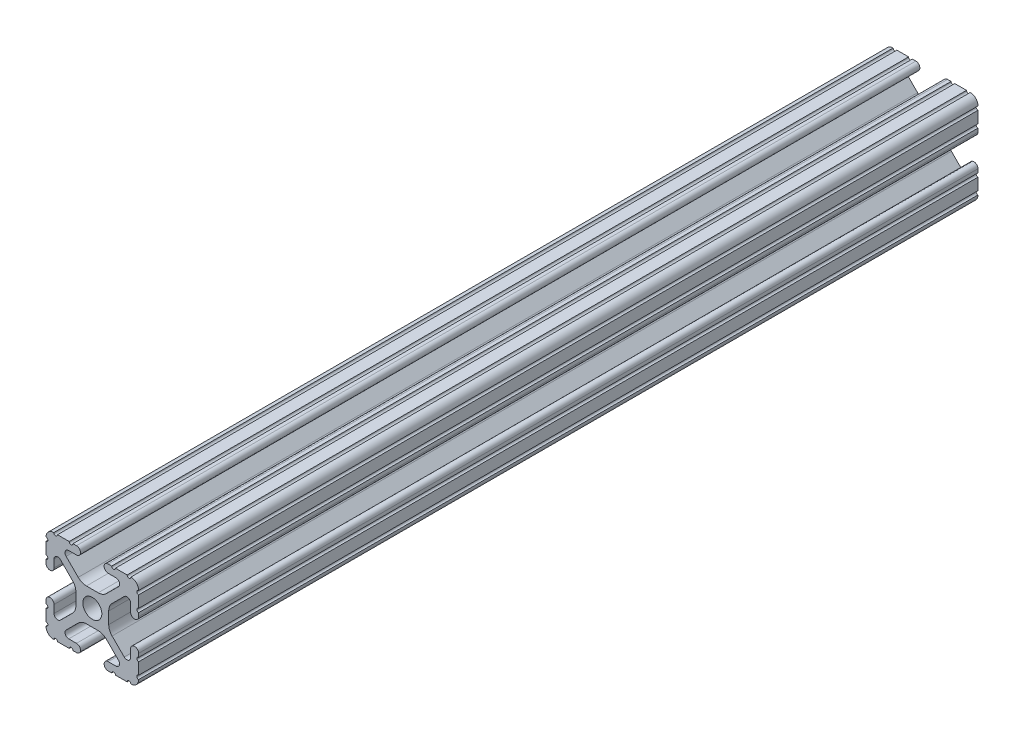
SolidWorks part; units mm, degrees
ref_plane "Front Plane" through (0, 0, 0) normal (0, 0, 1) x (1, 0, 0)
ref_plane "Top Plane" through (0, 0, 0) normal (0, 1, 0) x (1, 0, 0)
ref_plane "Right Plane" through (0, 0, 0) normal (1, 0, 0) x (0, 0, -1)
ref_plane "Plane1" through (0, 0, -25.4) normal (0, 0, -1) x (-1, 0, 0)
sketch "Sketch1" plane through (0, 0, -25.4) normal (0, 0, -1) x (-1, 0, 0)
  line L0 (12.7, -9.5504) -> (12.7, -6.3331)
  line L1 (12.7, -5.3171) -> (12.7, -4.3434)
  line L2 (10.4902, -4.3434) -> (10.4902, -6.4748)
  line L3 (8.7558, -7.1932) -> (5.4257, -3.8632)
  line L4 (4.4958, -1.6181) -> (4.4958, 1.6181)
  line L5 (5.4257, 3.8632) -> (8.7558, 7.1932)
  line L6 (10.4902, 6.4748) -> (10.4902, 4.3434)
  line L7 (12.7, 4.3434) -> (12.7, 5.3171)
  line L8 (12.7, 6.3331) -> (12.7, 9.5504)
  line L9 (9.5504, 12.7) -> (6.3331, 12.7)
  line L10 (5.3171, 12.7) -> (4.3434, 12.7)
  line L11 (4.3434, 10.4902) -> (6.4748, 10.4902)
  line L12 (7.1932, 8.7558) -> (3.8632, 5.4257)
  line L13 (1.6181, 4.4958) -> (-1.6181, 4.4958)
  line L14 (-3.8632, 5.4257) -> (-7.1932, 8.7558)
  line L15 (-6.4748, 10.4902) -> (-4.3434, 10.4902)
  line L16 (-4.3434, 12.7) -> (-5.3171, 12.7)
  line L17 (-6.3331, 12.7) -> (-9.5504, 12.7)
  line L18 (-12.7, 9.5504) -> (-12.7, 6.3331)
  line L19 (-12.7, 5.3171) -> (-12.7, 4.3434)
  line L20 (-10.4902, 4.3434) -> (-10.4902, 6.4748)
  line L21 (-8.7558, 7.1932) -> (-5.4257, 3.8632)
  line L22 (-4.4958, 1.6181) -> (-4.4958, -1.6181)
  line L23 (-5.4257, -3.8632) -> (-8.7558, -7.1932)
  line L24 (-10.4902, -6.4748) -> (-10.4902, -4.3434)
  line L25 (-12.7, -4.3434) -> (-12.7, -5.3171)
  line L26 (-12.7, -6.3331) -> (-12.7, -9.5504)
  line L27 (-9.5504, -12.7) -> (-6.3331, -12.7)
  line L28 (-5.3171, -12.7) -> (-4.3434, -12.7)
  line L29 (-4.3434, -10.4902) -> (-6.4748, -10.4902)
  line L30 (-7.1932, -8.7558) -> (-3.8632, -5.4257)
  line L31 (-1.6181, -4.4958) -> (1.6181, -4.4958)
  line L32 (3.8632, -5.4257) -> (7.1932, -8.7558)
  line L33 (6.4748, -10.4902) -> (4.3434, -10.4902)
  line L34 (4.3434, -12.7) -> (5.3171, -12.7)
  line L35 (6.3331, -12.7) -> (9.5504, -12.7)
  arc A0 (12.6998, -10.5664) -> (12.7, -9.5504) centre (12.7, -10.0584) cw
  arc A1 (12.7, -6.3331) -> (12.7, -5.3171) centre (12.7, -5.8251) cw
  arc A2 (12.7, -4.3434) -> (10.4902, -4.3434) centre (11.5951, -4.3434) ccw
  arc A3 (10.4902, -6.4748) -> (8.7558, -7.1932) centre (9.4742, -6.4748) cw
  arc A4 (5.4257, -3.8632) -> (4.4958, -1.6181) centre (7.6708, -1.6181) cw
  arc A5 (4.4958, 1.6181) -> (5.4257, 3.8632) centre (7.6708, 1.6181) cw
  arc A6 (8.7558, 7.1932) -> (10.4902, 6.4748) centre (9.4742, 6.4748) cw
  arc A7 (10.4902, 4.3434) -> (12.7, 4.3434) centre (11.5951, 4.3434) ccw
  arc A8 (12.7, 5.3171) -> (12.7, 6.3331) centre (12.7, 5.8251) cw
  arc A9 (12.7, 9.5504) -> (12.6998, 10.5664) centre (12.7, 10.0584) cw
  arc A10 (12.6998, 10.5664) -> (10.5664, 12.6998) centre (10.5918, 10.5918) ccw
  arc A11 (10.5664, 12.6998) -> (9.5504, 12.7) centre (10.0584, 12.7) cw
  arc A12 (6.3331, 12.7) -> (5.3171, 12.7) centre (5.8251, 12.7) cw
  arc A13 (4.3434, 12.7) -> (4.3434, 10.4902) centre (4.3434, 11.5951) ccw
  arc A14 (6.4748, 10.4902) -> (7.1932, 8.7558) centre (6.4748, 9.4742) cw
  arc A15 (3.8632, 5.4257) -> (1.6181, 4.4958) centre (1.6181, 7.6708) cw
  arc A16 (-1.6181, 4.4958) -> (-3.8632, 5.4257) centre (-1.6181, 7.6708) cw
  arc A17 (-7.1932, 8.7558) -> (-6.4748, 10.4902) centre (-6.4748, 9.4742) cw
  arc A18 (-4.3434, 10.4902) -> (-4.3434, 12.7) centre (-4.3434, 11.5951) ccw
  arc A19 (-5.3171, 12.7) -> (-6.3331, 12.7) centre (-5.8251, 12.7) cw
  arc A20 (-9.5504, 12.7) -> (-10.5664, 12.6998) centre (-10.0584, 12.7) cw
  arc A21 (-10.5664, 12.6998) -> (-12.6998, 10.5664) centre (-10.5918, 10.5918) ccw
  arc A22 (-12.6998, 10.5664) -> (-12.7, 9.5504) centre (-12.7, 10.0584) cw
  arc A23 (-12.7, 6.3331) -> (-12.7, 5.3171) centre (-12.7, 5.8251) cw
  arc A24 (-12.7, 4.3434) -> (-10.4902, 4.3434) centre (-11.5951, 4.3434) ccw
  arc A25 (-10.4902, 6.4748) -> (-8.7558, 7.1932) centre (-9.4742, 6.4748) cw
  arc A26 (-5.4257, 3.8632) -> (-4.4958, 1.6181) centre (-7.6708, 1.6181) cw
  arc A27 (-4.4958, -1.6181) -> (-5.4257, -3.8632) centre (-7.6708, -1.6181) cw
  arc A28 (-8.7558, -7.1932) -> (-10.4902, -6.4748) centre (-9.4742, -6.4748) cw
  arc A29 (-10.4902, -4.3434) -> (-12.7, -4.3434) centre (-11.5951, -4.3434) ccw
  arc A30 (-12.7, -5.3171) -> (-12.7, -6.3331) centre (-12.7, -5.8251) cw
  arc A31 (-12.7, -9.5504) -> (-12.6998, -10.5664) centre (-12.7, -10.0584) cw
  arc A32 (-12.6998, -10.5664) -> (-10.5664, -12.6998) centre (-10.5918, -10.5918) ccw
  arc A33 (-10.5664, -12.6998) -> (-9.5504, -12.7) centre (-10.0584, -12.7) cw
  arc A34 (-6.3331, -12.7) -> (-5.3171, -12.7) centre (-5.8251, -12.7) cw
  arc A35 (-4.3434, -12.7) -> (-4.3434, -10.4902) centre (-4.3434, -11.5951) ccw
  arc A36 (-6.4748, -10.4902) -> (-7.1932, -8.7558) centre (-6.4748, -9.4742) cw
  arc A37 (-3.8632, -5.4257) -> (-1.6181, -4.4958) centre (-1.6181, -7.6708) cw
  arc A38 (1.6181, -4.4958) -> (3.8632, -5.4257) centre (1.6181, -7.6708) cw
  arc A39 (7.1932, -8.7558) -> (6.4748, -10.4902) centre (6.4748, -9.4742) cw
  arc A40 (4.3434, -10.4902) -> (4.3434, -12.7) centre (4.3434, -11.5951) ccw
  arc A41 (5.3171, -12.7) -> (6.3331, -12.7) centre (5.8251, -12.7) cw
  arc A42 (9.5504, -12.7) -> (10.5664, -12.6998) centre (10.0584, -12.7) cw
  arc A43 (10.5664, -12.6998) -> (12.6998, -10.5664) centre (10.5918, -10.5918) ccw
  circle A44 centre (0, 0) radius 2.6035
extrude "Boss-Extrude1" add sketch "Sketch1" along normal blind 230.1875
